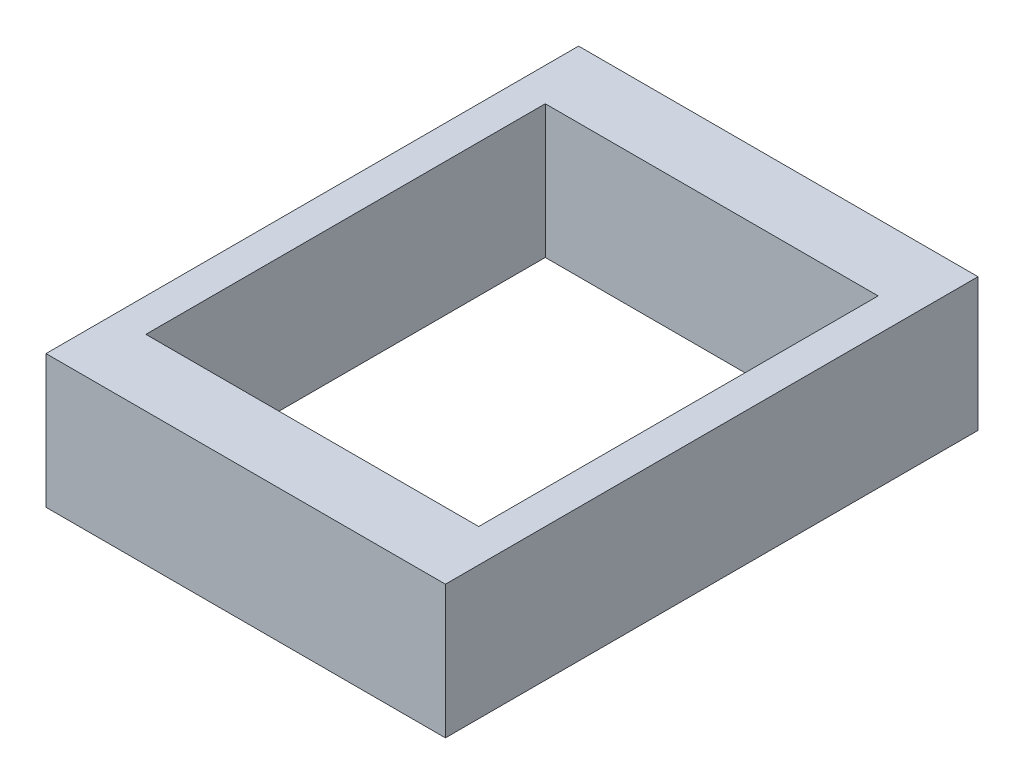
SolidWorks part; units mm, degrees
material "AISI 304"
ref_plane "Front Plane" through (0, 0, 0) normal (0, 0, 1) x (1, 0, 0)
ref_plane "Top Plane" through (0, 0, 0) normal (0, 1, 0) x (1, 0, 0)
ref_plane "Right Plane" through (0, 0, 0) normal (1, 0, 0) x (0, 0, -1)
sketch "Sketch1" plane through (0, 0, 0) normal (0, 1, 0) x (1, 0, 0)
  line L1 (-38.1, -50.8) -> (38.1, -50.8)
  line L2 (-38.1, -50.8) -> (-38.1, 50.8)
  line L3 (-38.1, 50.8) -> (38.1, 50.8)
  line L4 (38.1, -50.8) -> (38.1, 50.8)
  line L5 (-38.1, -50.8) -> (38.1, 50.8) construction
  line L6 (-38.1, 50.8) -> (38.1, -50.8) construction
  point P0 (0, 0)
  dimension "D1" = 101.6
  dimension "D2" = 76.2
extrude "Boss-Extrude1" add sketch "Sketch1" along normal blind 25.4
sketch "Sketch2" plane through (0, 25.4, 0) normal (0, 1, 0) x (1, 0, 0)
  line L1 (-31.75, -38.1) -> (31.75, -38.1)
  line L2 (-31.75, -38.1) -> (-31.75, 38.1)
  line L3 (-31.75, 38.1) -> (31.75, 38.1)
  line L4 (31.75, -38.1) -> (31.75, 38.1)
  line L5 (-31.75, -38.1) -> (31.75, 38.1) construction
  line L6 (-31.75, 38.1) -> (31.75, -38.1) construction
  point P0 (0, 0)
  dimension "D1" = 76.2
  dimension "D2" = 63.5
extrude "Cut-Extrude1" cut sketch "Sketch2" against normal through all
